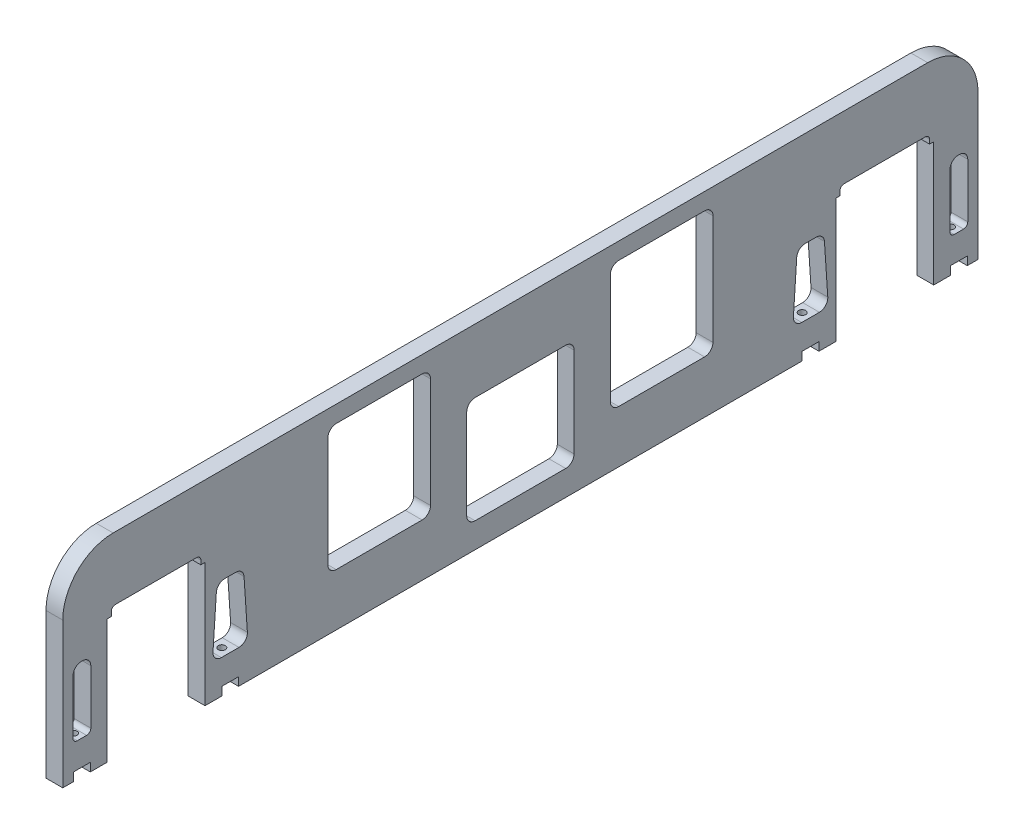
SolidWorks part; units mm, degrees
material "Alloy Steel"
ref_plane "Front Plane" through (0, 0, 0) normal (0, 0, 1) x (1, 0, 0)
ref_plane "Top Plane" through (0, 0, 0) normal (0, 1, 0) x (1, 0, 0)
ref_plane "Right Plane" through (0, 0, 0) normal (1, 0, 0) x (0, 0, -1)
sketch "Sketch1" plane through (0, 0, 0) normal (1, 0, 0) x (0, 0, -1)
  line L0 (0, 74.041) -> (0, 0) construction
  line L1 (173.228, 74.041) -> (173.228, 0)
  line L2 (-173.228, 74.041) -> (-173.228, 0)
  line L3 (156.464, 0) -> (173.228, 0)
  line L5 (156.464, 46.99) -> (156.464, 0)
  line L6 (-119.38, 0) -> (119.38, 0)
  line L7 (-137.922, 74.041) -> (-137.922, 0) construction
  line L8 (119.38, 46.99) -> (156.464, 46.99)
  line L9 (-156.464, 0) -> (-173.228, 0)
  line L10 (-119.38, 46.99) -> (-156.464, 46.99)
  line L11 (-119.38, 46.99) -> (-119.38, 0)
  line L12 (119.38, 46.99) -> (119.38, 0)
  line L13 (-156.464, 46.99) -> (-156.464, 0)
  line L16 (173.228, 74.041) -> (-173.228, 74.041)
  point P0 (0, 0)
  point P17 (-137.922, 46.99)
  dimension "D1" = 137.922
  dimension "D2" = 16.764
  dimension "D3" = 74.041
  dimension "D5" = 37.084
  dimension "D6" = 46.99
extrude "Boss-Extrude1" add sketch "Sketch1" along normal blind 6.35
fillet "Fillet1" radius 19.05 2 edges at (3.175, 74.041, -173.228) (3.175, 74.041, 173.228)
sketch "Sketch2" plane through (6.35, 0, 0) normal (1, 0, 0) x (0, 0, -1)
  line L0 (-156.464, 46.99) -> (-119.38, 46.99) construction
  line L1 (-154.8765, 46.99) -> (-120.9675, 46.99)
  line L2 (-154.8765, 46.99) -> (-154.8765, 50.165)
  line L3 (-154.8765, 50.165) -> (-120.9675, 50.165)
  line L4 (-120.9675, 46.99) -> (-120.9675, 50.165)
  dimension "D1" = 1.5875
  dimension "D2" = 1.5875
  dimension "D3" = 3.175
extrude "Cut-Extrude1" cut sketch "Sketch2" against normal through all
fillet "Fillet2" radius 1.5875 2 edges at (3.175, 50.165, 120.9675) (3.175, 50.165, 154.8765)
mirror "Mirror1" about plane through (0, 0, 0) normal (0, 0, 1) of "Fillet2", "Cut-Extrude1"
sketch "Sketch3" plane through (6.35, 0, 0) normal (1, 0, 0) x (0, 0, -1)
  line L0 (-119.38, 0) -> (119.38, 0) construction
  line L1 (-113.03, 0) -> (-106.68, 0)
  line L2 (-113.03, 0) -> (-113.03, 3.175)
  line L3 (-113.03, 3.175) -> (-106.68, 3.175)
  line L4 (-106.68, 0) -> (-106.68, 3.175)
  line L5 (-137.922, 50.165) -> (-137.922, 0) construction
  line L6 (-122.555, 50.165) -> (-153.289, 50.165) construction
  line L7 (-162.814, 0) -> (-169.164, 0)
  line L8 (-169.164, 0) -> (-169.164, 3.175)
  line L9 (-162.814, 3.175) -> (-169.164, 3.175)
  line L10 (-162.814, 0) -> (-162.814, 3.175)
  dimension "D1" = 6.35
  dimension "D2" = 6.35
  dimension "D3" = 3.175
extrude "Cut-Extrude2" cut sketch "Sketch3" against normal through all
mirror "Mirror2" about plane through (0, 0, 0) normal (0, 0, 1) of "Cut-Extrude2"
sketch "Sketch4" plane through (6.35, 0, 0) normal (1, 0, 0) x (0, 0, -1)
  line L0 (0, 0) -> (0, 74.041) construction
  line L1 (-106.68, 0) -> (106.68, 0) construction
  line L2 (154.178, 74.041) -> (-154.178, 74.041) construction
  line L3 (34.036, 67.691) -> (34.036, 19.812)
  line L4 (-72.898, 67.691) -> (-34.036, 67.691)
  line L5 (-72.898, 67.691) -> (-72.898, 19.812)
  line L6 (-72.898, 19.812) -> (-34.036, 19.812)
  line L7 (-34.036, 67.691) -> (-34.036, 19.812)
  line L8 (72.898, 67.691) -> (34.036, 67.691)
  line L9 (72.898, 67.691) -> (72.898, 19.812)
  line L10 (72.898, 19.812) -> (34.036, 19.812)
  line L12 (-20.32, 49.911) -> (20.32, 49.911)
  line L13 (-20.32, 49.911) -> (-20.32, 9.525)
  line L14 (-20.32, 9.525) -> (20.32, 9.525)
  line L15 (20.32, 49.911) -> (20.32, 9.525)
  dimension "D1" = 38.862
  dimension "D2" = 47.879
  dimension "D3" = 72.898
  dimension "D4" = 6.35
  dimension "D5" = 40.64
  dimension "D6" = 9.525
  dimension "D7" = 40.386
extrude "Cut-Extrude3" cut sketch "Sketch4" against normal through all
fillet "Fillet3" radius 3.175 12 edges at (3.175, 49.911, -20.32) (3.175, 49.911, 20.32) (3.175, 9.525, 20.32) (3.175, 9.525, -20.32) (3.175, 67.691, -72.898) (3.175, 19.812, -72.898) (3.175, 19.812, -34.036) (3.175, 67.691, -34.036) (3.175, 67.691, 72.898) (3.175, 67.691, 34.036) (3.175, 19.812, 34.036) (3.175, 19.812, 72.898)
sketch "Sketch5" plane through (6.35, 0, 0) normal (1, 0, 0) x (0, 0, -1)
  line L0 (156.464, 0) -> (162.814, 0) construction
  line L1 (169.3545, 12.7) -> (162.6235, 12.7)
  line L2 (169.3545, 12.7) -> (169.3545, 37.9413)
  line L3 (169.3545, 37.9413) -> (162.6235, 37.9413)
  line L4 (162.6235, 12.7) -> (162.6235, 37.9413)
  line L5 (165.989, 3.175) -> (165.989, 37.9413) construction
  line L6 (162.814, 3.175) -> (169.164, 3.175) construction
  line L7 (0, 0) -> (0, 74.041) construction
  line L8 (-106.68, 0) -> (106.68, 0) construction
  line L9 (154.178, 74.041) -> (-154.178, 74.041) construction
  line L10 (-169.3545, 37.9413) -> (-162.6235, 37.9413)
  line L11 (-169.3545, 12.7) -> (-162.6235, 12.7)
  line L12 (-169.3545, 12.7) -> (-169.3545, 37.9413)
  line L13 (-162.6235, 12.7) -> (-162.6235, 37.9413)
  line L14 (103.124, 12.7) -> (116.586, 12.7)
  line L15 (109.855, 3.175) -> (109.855, 37.9413) construction
  line L16 (106.68, 3.175) -> (113.03, 3.175) construction
  line L17 (104.8067, 37.9413) -> (114.9032, 37.9413)
  line L18 (104.8067, 37.9413) -> (103.124, 12.7)
  line L19 (-103.124, 12.7) -> (-116.586, 12.7)
  line L20 (114.9032, 37.9413) -> (116.586, 12.7)
  line L21 (-104.8067, 37.9413) -> (-114.9032, 37.9413)
  line L22 (-114.9032, 37.9413) -> (-116.586, 12.7)
  line L23 (-104.8067, 37.9413) -> (-103.124, 12.7)
  point P10 (165.989, 12.7)
  point P27 (109.855, 12.7)
  point P30 (109.855, 37.9413)
  dimension "D1" = 12.7
  dimension "D2" = 25.2413
  dimension "D3" = 6.731
  dimension "D4" = 13.462
  dimension "D5" = 10.0965
extrude "Cut-Extrude4" cut sketch "Sketch5" against normal through all
fillet "Fillet4" radius 3.175 12 edges at (3.175, 37.9413, 169.3545) (3.175, 37.9413, 162.6235) (3.175, 37.9413, -169.3545) (3.175, 37.9413, -162.6235) (3.175, 37.9413, -104.8067) (3.175, 37.9413, -114.9032) (3.175, 12.7, -116.586) (3.175, 12.7, -103.124) (3.175, 37.9413, 114.9032) (3.175, 37.9413, 104.8067) (3.175, 12.7, 103.124) (3.175, 12.7, 116.586)
fillet "Fillet5" radius 1.5875 4 edges at (3.175, 12.7, 162.6235) (3.175, 12.7, 169.3545) (3.175, 12.7, -162.6235) (3.175, 12.7, -169.3545)
scale "Scale to 1.6" [suppressed]
sketch "Sketch6" plane through (0, 3.175, 0) normal (0, -1, 0) x (1, 0, 0)
  line L0 (6.35, 165.989) -> (0, 165.989) construction
  line L1 (6.35, 162.814) -> (6.35, 169.164) construction
  line L2 (0, 162.814) -> (0, 169.164) construction
  line L3 (6.35, 109.855) -> (0, 109.855) construction
  line L4 (6.35, 106.68) -> (6.35, 113.03) construction
  line L5 (0, 106.68) -> (0, 113.03) construction
  line L6 (6.35, -109.855) -> (0, -109.855) construction
  line L7 (6.35, -106.68) -> (6.35, -113.03) construction
  line L8 (0, -106.68) -> (0, -113.03) construction
  line L9 (6.35, -165.989) -> (0, -165.989) construction
  line L10 (6.35, -162.814) -> (6.35, -169.164) construction
  line L11 (0, -162.814) -> (0, -169.164) construction
  point P12 (3.175, 165.989)
  point P13 (3.175, 109.855)
  point P26 (3.175, -109.855)
  point P27 (3.175, -165.989)
hole_wizard "#6-32 Tapped Hole1" positions "3DSketch1" profile "Sketch7" tap size "#6-32" standard "ANSI Inch"
sketch3d "3DSketch1"
  point P0 (3.175, 3.175, 165.989)
  point P3 (3.175, 3.175, 109.855)
  point P6 (3.175, 3.175, -109.855)
  point P9 (3.175, 3.175, -165.989)
sketch "Sketch7" plane through (3.175, 3.175, 165.989) normal (1, 0, 0) x (0, 0, -1)
  line L0 (0, 0) -> (0, 14.1477)
  line L1 (0, 14.1477) -> (1.3525, 13.335)
  line L2 (1.3525, 13.335) -> (1.3525, 0)
  line L5 (1.3525, 0) -> (0, 0)
  line L10 (0, 14.1477) -> (-1.3526, 13.335) construction
  line L11 (0, -6.35) -> (0, 107.95) construction
  dimension "Tap Drill Dia." = 2.7051
  dimension "Tap Drill Depth" = 13.335
  dimension "Drill Angle" = 118
cosmetic thread "Hole Thread1" parameters "D1"=7.0104, "D2"=3.5052
cosmetic thread "Hole Thread2" parameters "D1"=7.0104, "D2"=3.5052
cosmetic thread "Hole Thread3" parameters "D1"=7.0104, "D2"=3.5052
cosmetic thread "Hole Thread4" parameters "D1"=7.0104, "D2"=3.5052
